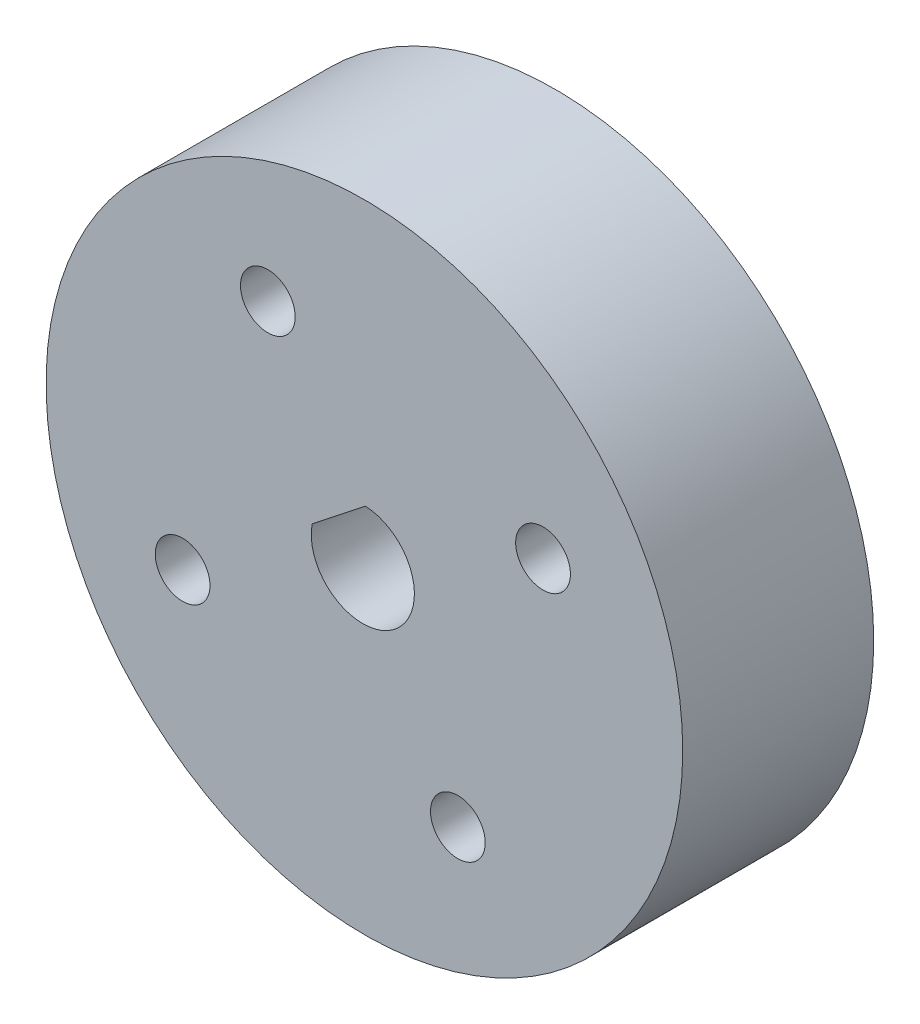
SolidWorks part; units mm, degrees
ref_plane "前视基准面" through (0, 0, 0) normal (0, 0, 1) x (1, 0, 0)
ref_plane "上视基准面" through (0, 0, 0) normal (0, 1, 0) x (1, 0, 0)
ref_plane "右视基准面" through (0, 0, 0) normal (1, 0, 0) x (0, 0, -1)
sketch "草图1" plane through (0, 0, 0) normal (0, 0, 1) x (1, 0, 0)
  circle A0 centre (0, 0) radius 25
  dimension "D1" = 50
extrude "凸台-拉伸1" add sketch "草图1" along normal blind 15
sketch "草图2" plane through (0, 0, 0) normal (0, 0, -1) x (-1, 0, 0)
  circle A0 centre (0, 0) radius 15.2
  dimension "D1" = 30.4
extrude "切除-拉伸1" cut sketch "草图2" against normal blind 8
sketch "草图3" plane through (0, 0, 15) normal (0, 0, 1) x (1, 0, 0)
  circle A0 centre (-14.278, -7.3139) radius 2.15
  circle A1 centre (-7.5861, 14.3013) radius 2.15
  circle A2 centre (14.0291, 7.6093) radius 2.15
  circle A3 centre (7.3372, -14.0059) radius 2.15
extrude "切除-拉伸2" cut sketch "草图3" against normal blind 10
sketch "草图4" plane through (0, 0, 15) normal (0, 0, 1) x (1, 0, 0)
  line L0 (0.0808, 4.1925) -> (-4.1051, 0.8942)
  circle A0 centre (-0.1245, 0.1477) radius 4.05
extrude "切除-拉伸3" cut sketch "草图4" against normal through all contours L0 A0
